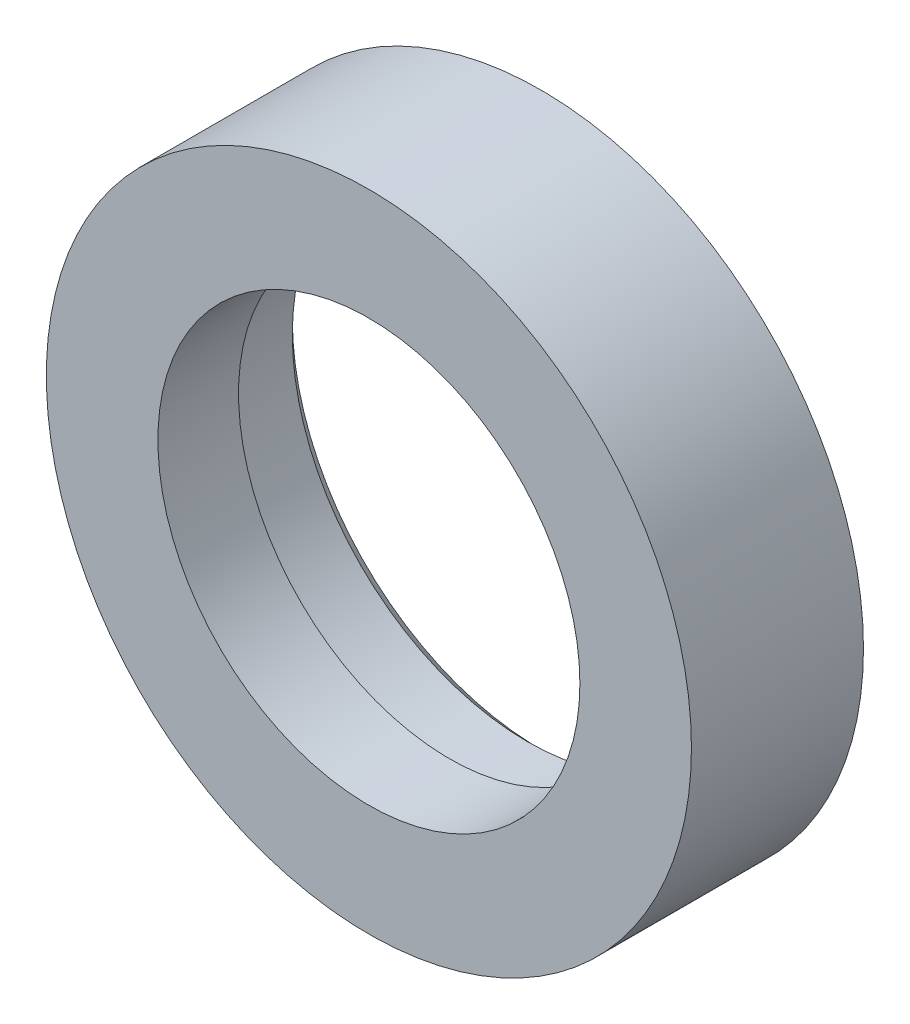
SolidWorks part; units mm, degrees
ref_plane "Plan de face" through (0, 0, 0) normal (0, 0, 1) x (1, 0, 0)
ref_plane "Plan de dessus" through (0, 0, 0) normal (0, 1, 0) x (1, 0, 0)
ref_plane "Plan de droite" through (0, 0, 0) normal (1, 0, 0) x (0, 0, -1)
sketch "Esquisse1" plane through (0, 0, 0) normal (0, 1, 0) x (1, 0, 0)
  line L0 (0, 0) -> (0, 86.9992) construction
  line L1 (24, 5.6651) -> (24, 18.4651)
  line L2 (24, 18.4651) -> (17.5, 18.4651)
  line L3 (17.5, 18.4651) -> (17.5, 11.6651)
  line L4 (17.5, 11.6651) -> (15.7, 11.6651)
  line L5 (15.7, 11.6651) -> (15.7, 5.6651)
  line L6 (15.7, 5.6651) -> (24, 5.6651)
  dimension "D1" = 24
  dimension "D2" = 15.7
  dimension "D3" = 17.5
  dimension "D4" = 12.8
  dimension "D5" = 6
revolve "Révolution1" add sketch "Esquisse1" angle 360 about L0
chamfer "Chanfrein2" distance 1 angle 45 1 edges at (17.5, 0, -18.4651)
